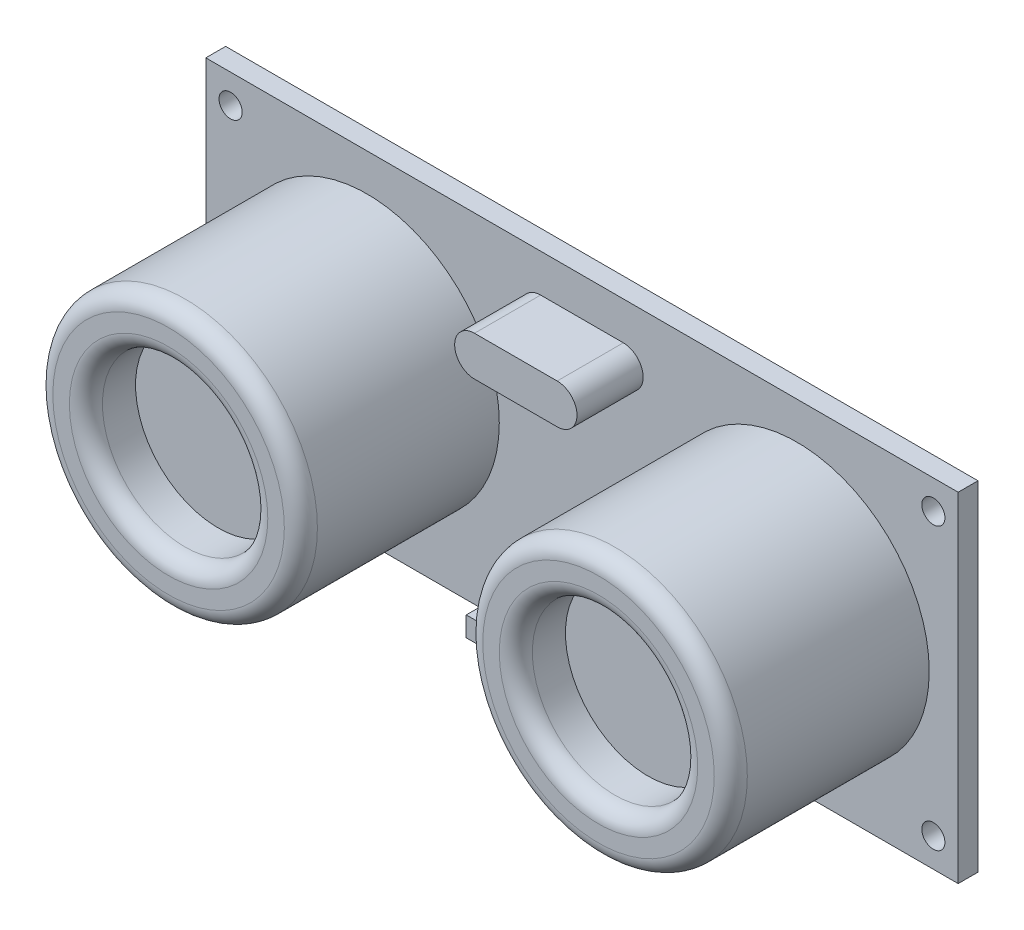
SolidWorks part; units mm, degrees
ref_plane "前视基准面" through (0, 0, 0) normal (0, 0, 1) x (1, 0, 0)
ref_plane "上视基准面" through (0, 0, 0) normal (0, 1, 0) x (1, 0, 0)
ref_plane "右视基准面" through (0, 0, 0) normal (1, 0, 0) x (0, 0, -1)
sketch "草图1" plane through (0, 0, 0) normal (0, 0, 1) x (1, 0, 0)
  line L1 (-22.75, -10.25) -> (22.75, -10.25)
  line L2 (-22.75, -10.25) -> (-22.75, 10.25)
  line L3 (-22.75, 10.25) -> (22.75, 10.25)
  line L4 (22.75, -10.25) -> (22.75, 10.25)
  line L5 (-22.75, -10.25) -> (22.75, 10.25) construction
  line L6 (-22.75, 10.25) -> (22.75, -10.25) construction
  line L7 (-21.25, -8.5) -> (21.25, -8.5) construction
  line L8 (-21.25, -8.5) -> (-21.25, 8.5) construction
  line L9 (-21.25, 8.5) -> (21.25, 8.5) construction
  line L10 (21.25, -8.5) -> (21.25, 8.5) construction
  line L11 (-21.25, -8.5) -> (21.25, 8.5) construction
  line L12 (-21.25, 8.5) -> (21.25, -8.5) construction
  circle A0 centre (21.25, 8.5) radius 0.7
  circle A1 centre (-21.25, 8.5) radius 0.7
  circle A2 centre (-21.25, -8.5) radius 0.7
  circle A3 centre (21.25, -8.5) radius 0.7
  point P0 (0, 0)
  point P6 (0, 0)
  dimension "D5" = 1.4
  dimension "D1" = 45.5
  dimension "D2" = 20.5
  dimension "D3" = 17
  dimension "D4" = 42.5
extrude "凸台-拉伸1" add sketch "草图1" along normal blind 1.2
sketch "草图2" plane through (0, 0, 1.2) normal (0, 0, 1) x (1, 0, 0)
  line L0 (0, 10.25) -> (0, -10.25) construction
  line L1 (22.75, 10.25) -> (-22.75, 10.25) construction
  line L2 (-22.75, -10.25) -> (22.75, -10.25) construction
  circle A0 centre (-13, 0) radius 8
  circle A1 centre (13, 0) radius 8
  dimension "D2" = 16
  dimension "D1" = 26
extrude "凸台-拉伸2" add sketch "草图2" along normal blind 12
sketch "草图3" plane through (0, 0, 13.2) normal (0, 0, 1) x (1, 0, 0)
  circle A0 centre (-13, 0) radius 5
  circle A1 centre (13, 0) radius 5
  dimension "D1" = 10
extrude "切除-拉伸1" cut sketch "草图3" against normal blind 3
fillet "圆角1" radius 1 4 edges at (21, 0, 13.2) (18, 0, 13.2) (-5, 0, 13.2) (-8, 0, 13.2)
sketch "草图4" plane through (0, 0, 1.2) normal (0, 0, 1) x (1, 0, 0)
  line L0 (-2.5, 6.75) -> (2.5, 6.75) construction
  line L1 (-2.5, 7.95) -> (2.5, 7.95)
  line L2 (-2.5, 5.55) -> (2.5, 5.55)
  line L3 (22.75, 10.25) -> (-22.75, 10.25) construction
  arc A0 (-2.5, 7.95) -> (-2.5, 5.55) centre (-2.5, 6.75) ccw
  arc A1 (2.5, 5.55) -> (2.5, 7.95) centre (2.5, 6.75) ccw
  point P2 (0, 6.75)
  dimension "D2" = 1.2
  dimension "D1" = 5
  dimension "D3" = 3.5
extrude "凸台-拉伸3" add sketch "草图4" along normal blind 4
sketch "草图5" plane through (0, 0, 1.2) normal (0, 0, 1) x (1, 0, 0)
  line L0 (-22.75, -10.25) -> (22.75, -10.25) construction
  line L1 (-4, -8.05) -> (4, -8.05)
  line L2 (-4, -8.05) -> (-4, -9.25)
  line L3 (-4, -9.25) -> (4, -9.25)
  line L4 (4, -8.05) -> (4, -9.25)
  point P4 (0, -8.05)
  dimension "D1" = 1
  dimension "D2" = 8
  dimension "D3" = 1.2
extrude "凸台-拉伸4" add sketch "草图5" along normal blind 3
